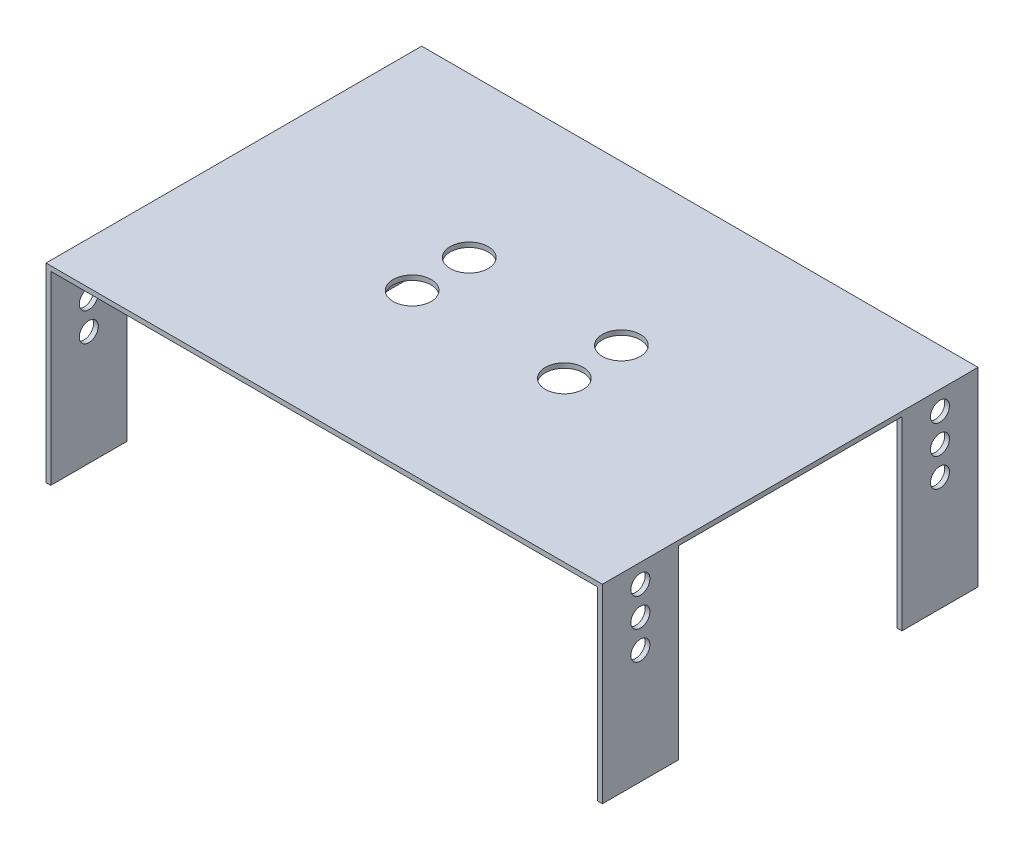
SolidWorks part; units mm, degrees
ref_plane "Front Plane" through (0, 0, 0) normal (0, 0, 1) x (1, 0, 0)
ref_plane "Top Plane" through (0, 0, 0) normal (0, 1, 0) x (1, 0, 0)
ref_plane "Right Plane" through (0, 0, 0) normal (1, 0, 0) x (0, 0, -1)
sketch "Sketch1" plane through (0, 0, 0) normal (0, 1, 0) x (1, 0, 0)
  line L1 (-297.5, 197.5) -> (287.5, 197.5)
  line L2 (-297.5, 197.5) -> (-297.5, -197.5)
  line L3 (-297.5, -197.5) -> (287.5, -197.5)
  line L4 (287.5, 197.5) -> (287.5, -197.5)
  line L7 (-217.5, 117.5) -> (207.5, 117.5)
  line L8 (-217.5, 117.5) -> (-217.5, -117.5)
  line L9 (-217.5, -117.5) -> (207.5, -117.5)
  line L10 (207.5, 117.5) -> (207.5, -117.5)
  point P0 (0, 0)
  point P6 (0, 0)
  dimension "D1" = 395
  dimension "D2" = 585
  dimension "D3" = 235
  dimension "D4" = 425
  dimension "D5" = 217.5
  dimension "D6" = 117.5
extrude "Boss-Extrude1" add sketch "Sketch1" along normal mid plane 5
sketch "Sketch2" plane through (-297.5, 0, 0) normal (-1, 0, 0) x (0, 0, 1)
  line L0 (-197.5, 2.5) -> (-117.5012, 2.5)
  line L1 (-197.5, 2.5) -> (197.5, 2.5) construction
  line L2 (-117.5012, 2.5) -> (-117.5012, -197.5)
  line L3 (-117.5012, -197.5) -> (-197.5, -197.5)
  line L4 (-197.5, -197.5) -> (-197.5, 2.5)
  dimension "D1" = 200
extrude "Boss-Extrude2" add sketch "Sketch2" against normal blind 5
mirror "Mirror1" about plane through (0, 0, 0) normal (0, 0, 1) of "Boss-Extrude2"
ref_plane "Plane1" through (-5, 0, 0) normal (1, 0, 0) x (0, 0, -1)
mirror "Mirror5" about plane through (-5, 0, 0) normal (1, 0, 0) of "Mirror1", "Boss-Extrude2"
sketch "Sketch5" plane through (-297.5, 0, 0) normal (-1, 0, 0) x (0, 0, 1)
  line L0 (-197.5, 2.5) -> (197.5, 2.5) construction
  circle A0 centre (-157.5006, -17.5) radius 10
  circle A1 centre (-157.5006, -47.5) radius 10
  circle A2 centre (-157.5006, -77.5) radius 10
  circle A3 centre (157.5006, -17.5) radius 10
  circle A4 centre (157.5006, -47.5) radius 10
  circle A5 centre (157.5006, -77.5) radius 10
  dimension "D2" = 20
  dimension "D3" = 20
  dimension "D1" = 20
  dimension "D4" = 20
  dimension "D5" = 315.0012
extrude "Cut-Extrude2" cut sketch "Sketch5" against normal through all and the other way through all
sketch "Sketch7" plane through (0, 2.5, 0) normal (0, 1, 0) x (1, 0, 0)
  line L0 (-217.5, 117.5) -> (-217.5, -117.5) construction
  line L1 (-217.5, 117.5) -> (207.5, 117.5)
  line L2 (-217.5, 117.5) -> (-217.5, -117.5)
  line L3 (-217.5, -117.5) -> (207.5, -117.5)
  line L4 (207.5, 117.5) -> (207.5, -117.5)
  point P0 (0, 0)
extrude "Boss-Extrude4" add sketch "Sketch7" against normal blind 5
sketch "Sketch8" plane through (0, 2.5, 0) normal (0, 1, 0) x (1, 0, 0)
  line L0 (-1000, 0) -> (49000, 0) construction
  line L1 (0, -1000) -> (0, 49000) construction
  circle A0 centre (-80, 30) radius 20
  circle A1 centre (80, 30) radius 20
  circle A2 centre (80, -30) radius 20
  circle A3 centre (-80, -30) radius 20
  dimension "D1" = 40
  dimension "D2" = 80
  dimension "D3" = 30
extrude "Cut-Extrude3" cut sketch "Sketch8" against normal blind 10
